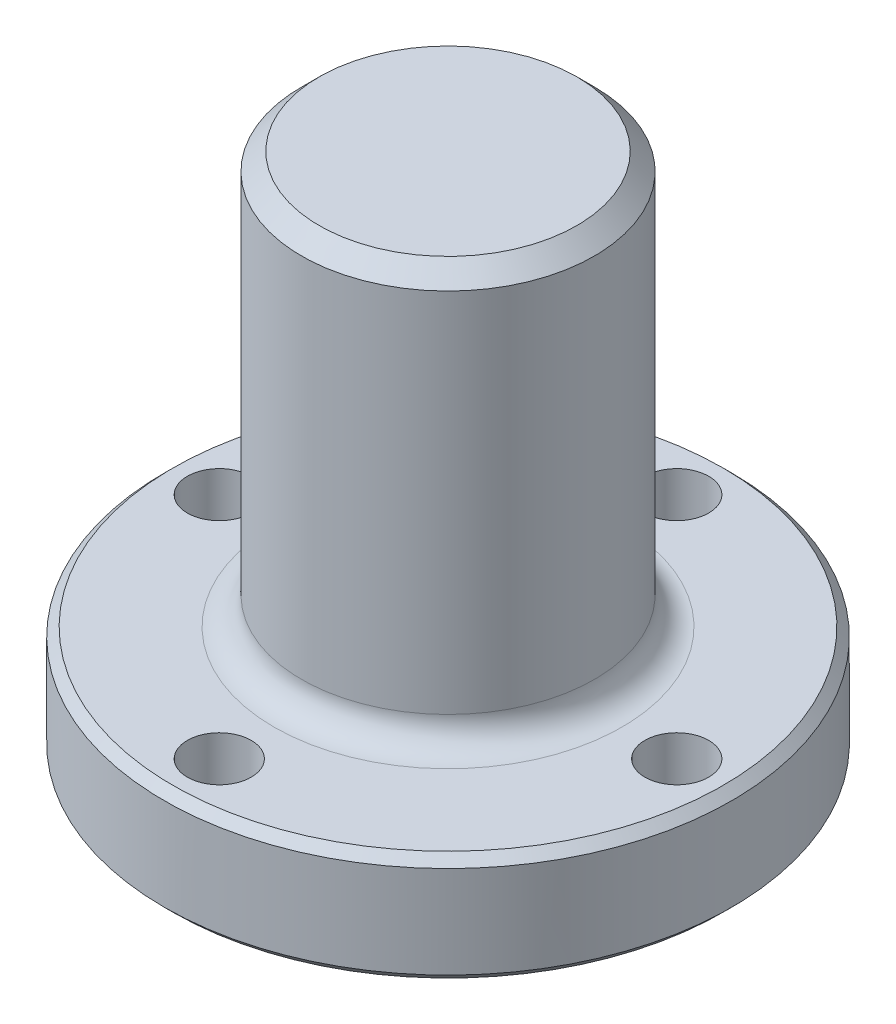
SolidWorks part; units mm, degrees
ref_plane "Front Plane" through (0, 0, 0) normal (1, 0, 0) x (0, 1, 0)
ref_plane "Top Plane" through (0, 0, 0) normal (0, 0, 1) x (0, 1, 0)
ref_plane "Right Plane" through (0, 0, 0) normal (0, 1, 0) x (-1, 0, 0)
sketch "Sketch1" plane through (0, 0, 0) normal (0, 0, 1) x (0, 1, 0)
  line L0 (-25.0317, 0) -> (-25.0317, 8.7122)
  line L1 (-25.0317, 8.7122) -> (-20.2057, 8.7122)
  line L2 (-20.2057, 8.7122) -> (-20.2057, 24.6126)
  line L3 (-20.2057, 24.6126) -> (-10.6807, 24.6126)
  line L4 (-10.6807, 24.6126) -> (-10.6807, 12.7)
  line L5 (-10.6807, 12.7) -> (25.0317, 12.7)
  line L6 (25.0317, 12.7) -> (25.0317, 0)
  line L7 (25.0317, 0) -> (-25.0317, 0)
  line L8 (-50.4317, 0) -> (50.4317, 0) construction
revolve "Revolve1" add sketch "Sketch1" angle 360 about L8
fillet "Fillet1" radius 2.3876 1 edges at (0, -10.6807, -12.7)
chamfer "Chamfer1" distance 0.762 angle 45 3 edges at (0, -10.6807, -24.6126) (0, -20.2057, -24.6126) (0, -25.0317, -8.7122)
chamfer "Chamfer2" distance 1.524 angle 45 1 edges at (0, 25.0317, -12.7)
sketch "Sketch2" plane through (0, 0, 0) normal (0, 1, 0) x (-1, 0, 0)
  circle A0 centre (19.8374, 0) radius 2.7686
  circle A1 centre (0, 19.8374) radius 2.7686
  circle A2 centre (-19.8374, 0) radius 2.7686
  circle A3 centre (0, -19.8374) radius 2.7686
extrude "Cut-Extrude2" cut sketch "Sketch2" against normal blind 10.6807 from offset 10.6807
